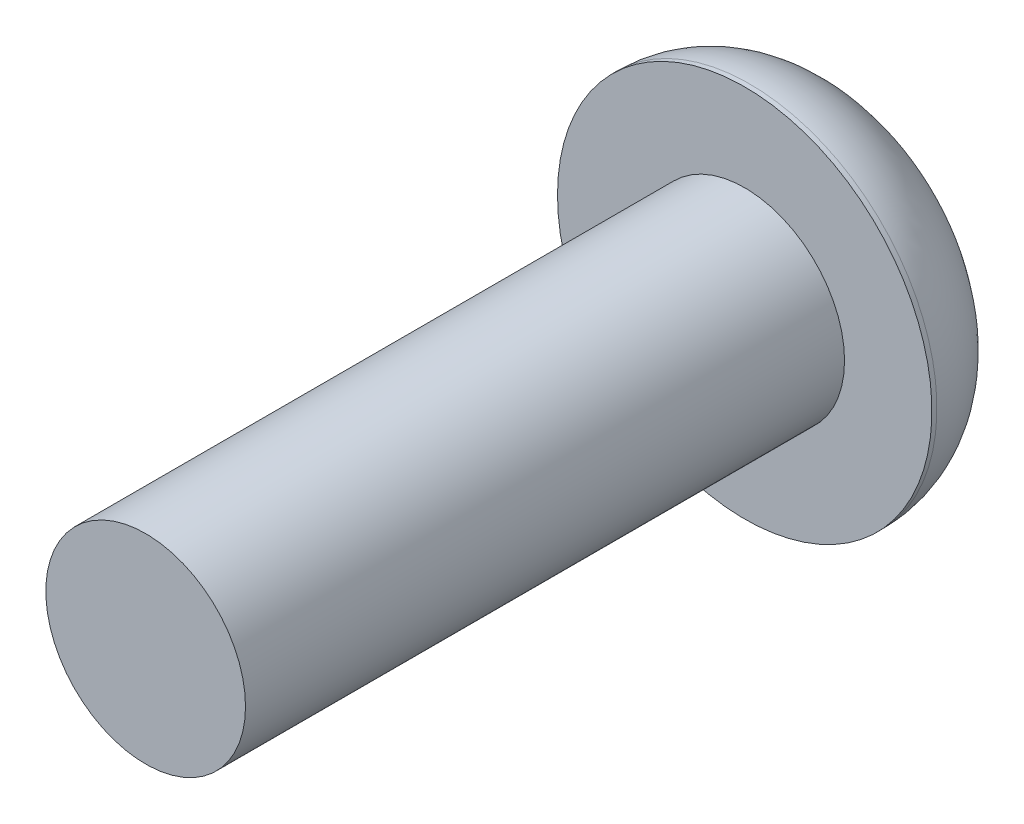
SolidWorks part; units mm, degrees
ref_plane "前视基准面" through (0, 0, 0) normal (0, 0, 1) x (1, 0, 0)
ref_plane "上视基准面" through (0, 0, 0) normal (0, 1, 0) x (1, 0, 0)
ref_plane "右视基准面" through (0, 0, 0) normal (1, 0, 0) x (0, 0, -1)
sketch "草图1" plane through (0, 0, 0) normal (0, 0, 1) x (1, 0, 0)
  circle A0 centre (0, 0) radius 2
extrude "凸台-拉伸1" add sketch "草图1" along normal blind 12
sketch "草图2" plane through (0, 0, 0) normal (0, 0, -1) x (-1, 0, 0)
  circle A0 centre (0, 0) radius 3.75
extrude "凸台-拉伸2" add sketch "草图2" along normal blind 2.1
fillet "圆角1" radius 2 1 edges at (-3.75, 0, -2.1)
